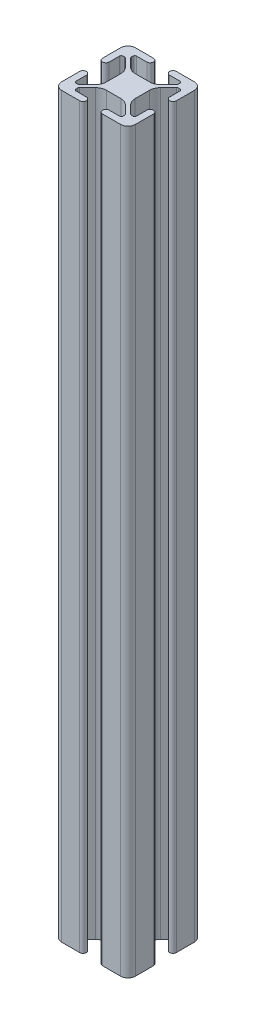
SolidWorks part; units mm, degrees
ref_plane "前视基准面" through (0, 0, 0) normal (0, 0, 1) x (1, 0, 0)
ref_plane "上视基准面" through (0, 0, 0) normal (0, 1, 0) x (1, 0, 0)
ref_plane "右视基准面" through (0, 0, 0) normal (1, 0, 0) x (0, 0, -1)
sketch "草图1" plane through (0, 0, 0) normal (0, 1, 0) x (1, 0, 0)
  line L0 (-1.0428, -10.0859) -> (3.8572, -10.0859)
  line L1 (1.0762, -11.8859) -> (3.8572, -11.8859)
  line L2 (2.8854, -15.3072) -> (0.7226, -13.1443)
  line L3 (2.1786, -16.0141) -> (0.0157, -13.8512)
  line L4 (-3.0428, -12.0859) -> (-3.0428, -16.9859)
  line L5 (-1.2428, -14.2048) -> (-1.2428, -16.9859)
  line L6 (-0.7428, -13.7048) -> (-0.3378, -13.7048)
  line L7 (0.5762, -12.3859) -> (0.5762, -12.7908)
  line L8 (-1.0428, -30.0859) -> (3.8572, -30.0859)
  line L9 (1.0762, -28.2859) -> (3.8572, -28.2859)
  line L10 (2.8854, -24.8645) -> (0.7226, -27.0274)
  line L11 (2.1786, -24.1577) -> (0.0157, -26.3205)
  line L12 (-3.0428, -28.0859) -> (-3.0428, -23.1859)
  line L13 (-1.2428, -25.9669) -> (-1.2428, -23.1859)
  line L14 (-0.7428, -26.4669) -> (-0.3378, -26.4669)
  line L15 (0.5762, -27.7859) -> (0.5762, -27.3809)
  line L16 (14.9572, -10.0859) -> (10.0572, -10.0859)
  line L17 (12.8383, -11.8859) -> (10.0572, -11.8859)
  line L18 (11.029, -15.3072) -> (13.1919, -13.1443)
  line L19 (11.7359, -16.0141) -> (13.8988, -13.8512)
  line L20 (16.9572, -12.0859) -> (16.9572, -16.9859)
  line L21 (15.1572, -14.2048) -> (15.1572, -16.9859)
  line L22 (14.6572, -13.7048) -> (14.2523, -13.7048)
  line L23 (13.3383, -12.3859) -> (13.3383, -12.7908)
  line L24 (14.9572, -30.0859) -> (10.0572, -30.0859)
  line L25 (12.8383, -28.2859) -> (10.0572, -28.2859)
  line L26 (11.029, -24.8645) -> (13.1919, -27.0274)
  line L27 (11.7359, -24.1577) -> (13.8988, -26.3205)
  line L28 (16.9572, -28.0859) -> (16.9572, -23.1859)
  line L29 (15.1572, -25.9669) -> (15.1572, -23.1859)
  line L30 (14.6572, -26.4669) -> (14.2523, -26.4669)
  line L31 (13.3383, -27.7859) -> (13.3383, -27.3809)
  line L32 (5.0068, -16.1859) -> (8.9077, -16.1859)
  line L33 (10.8572, -18.1354) -> (10.8572, -22.0363)
  line L34 (3.0572, -18.1354) -> (3.0572, -22.0363)
  line L35 (5.0068, -23.9859) -> (8.9077, -23.9859)
  circle A0 centre (6.9572, -20.0859) radius 2.5
  arc A1 (2.8854, -15.3072) -> (5.0068, -16.1859) centre (5.0068, -13.1859) ccw
  arc A2 (3.0572, -18.1354) -> (2.1786, -16.0141) centre (0.0572, -18.1354) ccw
  arc A3 (3.8572, -11.8859) -> (3.8572, -10.0859) centre (3.8572, -10.9859) ccw
  arc A4 (0.5762, -12.7908) -> (0.7226, -13.1443) centre (1.0762, -12.7908) ccw
  arc A5 (0.0157, -13.8512) -> (-0.3378, -13.7048) centre (-0.3378, -14.2048) ccw
  arc A6 (-3.0428, -16.9859) -> (-1.2428, -16.9859) centre (-2.1428, -16.9859) ccw
  arc A7 (-1.0428, -10.0859) -> (-3.0428, -12.0859) centre (-1.0428, -12.0859) ccw
  arc A8 (-0.7428, -13.7048) -> (-1.2428, -14.2048) centre (-0.7428, -14.2048) ccw
  arc A9 (1.0762, -11.8859) -> (0.5762, -12.3859) centre (1.0762, -12.3859) ccw
  arc A10 (5.0068, -23.9859) -> (2.8854, -24.8645) centre (5.0068, -26.9859) ccw
  arc A11 (2.1786, -24.1577) -> (3.0572, -22.0363) centre (0.0572, -22.0363) ccw
  arc A12 (3.8572, -30.0859) -> (3.8572, -28.2859) centre (3.8572, -29.1859) ccw
  arc A13 (0.7226, -27.0274) -> (0.5762, -27.3809) centre (1.0762, -27.3809) ccw
  arc A14 (-0.3378, -26.4669) -> (0.0157, -26.3205) centre (-0.3378, -25.9669) ccw
  arc A15 (-1.2428, -23.1859) -> (-3.0428, -23.1859) centre (-2.1428, -23.1859) ccw
  arc A16 (-3.0428, -28.0859) -> (-1.0428, -30.0859) centre (-1.0428, -28.0859) ccw
  arc A17 (-1.2428, -25.9669) -> (-0.7428, -26.4669) centre (-0.7428, -25.9669) ccw
  arc A18 (0.5762, -27.7859) -> (1.0762, -28.2859) centre (1.0762, -27.7859) ccw
  arc A19 (8.9077, -16.1859) -> (11.029, -15.3072) centre (8.9077, -13.1859) ccw
  arc A20 (11.7359, -16.0141) -> (10.8572, -18.1354) centre (13.8572, -18.1354) ccw
  arc A21 (10.0572, -10.0859) -> (10.0572, -11.8859) centre (10.0572, -10.9859) ccw
  arc A22 (13.1919, -13.1443) -> (13.3383, -12.7908) centre (12.8383, -12.7908) ccw
  arc A23 (14.2523, -13.7048) -> (13.8988, -13.8512) centre (14.2523, -14.2048) ccw
  arc A24 (15.1572, -16.9859) -> (16.9572, -16.9859) centre (16.0572, -16.9859) ccw
  arc A25 (16.9572, -12.0859) -> (14.9572, -10.0859) centre (14.9572, -12.0859) ccw
  arc A26 (15.1572, -14.2048) -> (14.6572, -13.7048) centre (14.6572, -14.2048) ccw
  arc A27 (13.3383, -12.3859) -> (12.8383, -11.8859) centre (12.8383, -12.3859) ccw
  arc A28 (11.029, -24.8645) -> (8.9077, -23.9859) centre (8.9077, -26.9859) ccw
  arc A29 (10.8572, -22.0363) -> (11.7359, -24.1577) centre (13.8572, -22.0363) ccw
  arc A30 (10.0572, -28.2859) -> (10.0572, -30.0859) centre (10.0572, -29.1859) ccw
  arc A31 (13.3383, -27.3809) -> (13.1919, -27.0274) centre (12.8383, -27.3809) ccw
  arc A32 (13.8988, -26.3205) -> (14.2523, -26.4669) centre (14.2523, -25.9669) ccw
  arc A33 (16.9572, -23.1859) -> (15.1572, -23.1859) centre (16.0572, -23.1859) ccw
  arc A34 (14.9572, -30.0859) -> (16.9572, -28.0859) centre (14.9572, -28.0859) ccw
  arc A35 (14.6572, -26.4669) -> (15.1572, -25.9669) centre (14.6572, -25.9669) ccw
  arc A36 (12.8383, -28.2859) -> (13.3383, -27.7859) centre (12.8383, -27.7859) ccw
extrude "凸台-拉伸1" add sketch "草图1" along normal blind 200 contours L32 A19 L18 A22 L23 A27 L17 A21 L16 A25 L20 A24 L21 A26 L22 A23 L19 A20 L33 A29 L27 A32 L30 A35 L29 A33 L28 A34 L24 A30 L25 A36 L31 A31 L26 A28 L35 A10 L10 A13 L15 A18 L9 A12 L8 A16 L12 A15 L13 A17 L14 A14 L11 A11 L34 A2 L3 A5 L6 A8 L5 A6 L4 A7 L0 A3 L1 A9 L7 A4 L2 A1
ref_plane "基准面1" through (0, 100, 0) normal (0, 1, 0) x (1, 0, 0)
ref_plane "基准面2" through (6.9572, 0, 0) normal (-1, 0, 0) x (0, 0, 1)
